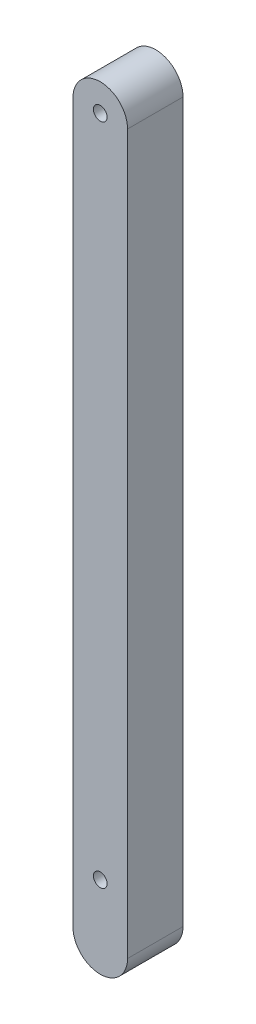
SolidWorks part; units mm, degrees
ref_plane "Front Plane" through (0, 0, 0) normal (0, 0, 1) x (1, 0, 0)
ref_plane "Top Plane" through (0, 0, 0) normal (0, 1, 0) x (1, 0, 0)
ref_plane "Right Plane" through (0, 0, 0) normal (1, 0, 0) x (0, 0, -1)
sketch "Sketch1" plane through (0, 0, 0) normal (0, 0, 1) x (1, 0, 0)
  line L0 (0, 63.6098) -> (0, -94.3902) construction
  line L1 (6, 63.6098) -> (6, -94.3902)
  line L2 (-6, 63.6098) -> (-6, -94.3902)
  arc A0 (6, 63.6098) -> (-6, 63.6098) centre (0, 63.6098) ccw
  arc A1 (-6, -94.3902) -> (6, -94.3902) centre (0, -94.3902) ccw
  circle A4 centre (0, -82.3902) radius 1.5
  circle A5 centre (0, 63.6098) radius 1.5
  point P3 (0, -15.3902)
  point P8 (0, -100.3902)
  point P13 (0, 69.6098)
  dimension "D1" = 6
  dimension "D3" = 18
  dimension "D4" = 3
  dimension "D2" = 3
  dimension "D5" = 170
extrude "Boss-Extrude1" add sketch "Sketch1" along normal blind 12.2
